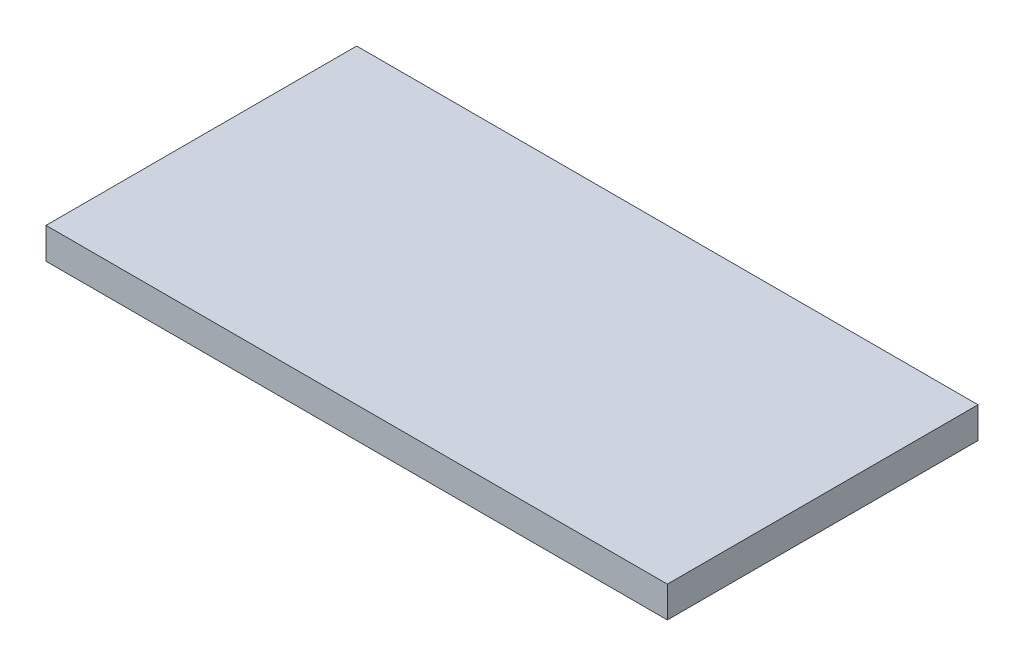
SolidWorks part; units mm, degrees
ref_plane "Front Plane" through (0, 0, 0) normal (0, 0, 1) x (1, 0, 0)
ref_plane "Top Plane" through (0, 0, 0) normal (0, 1, 0) x (1, 0, 0)
ref_plane "Right Plane" through (0, 0, 0) normal (1, 0, 0) x (0, 0, -1)
sketch "Sketch1" plane through (0, 0, 0) normal (0, 1, 0) x (1, 0, 0)
  line L1 (-1000, 500) -> (1000, 500)
  line L2 (-1000, 500) -> (-1000, -500)
  line L3 (-1000, -500) -> (1000, -500)
  line L4 (1000, 500) -> (1000, -500)
  line L5 (-1000, 500) -> (1000, -500) construction
  line L6 (-1000, -500) -> (1000, 500) construction
  point P0 (0, 0)
  dimension "D1" = 2000
  dimension "D2" = 1000
extrude "Boss-Extrude1" add sketch "Sketch1" along normal blind 100
sketch "Sketch2" plane through (0, 0, 0) normal (0, -1, 0) x (1, 0, 0)
  line L0 (-1000, 400) -> (-900, 400)
  line L1 (-1000, -500) -> (-1000, 500) construction
  line L2 (-900, 400) -> (-900, 500)
  line L3 (-1000, 500) -> (1000, 500) construction
  circle A0 centre (-900, 400) radius 63.8059
  point P8 (0, 0)
  point P10 (0, 0)
  dimension "D1" = 100
  dimension "D2" = 100
sketch "Sketch4" plane through (0, 0, 0) normal (0, -1, 0) x (1, 0, 0)
extrude "Cut-Extrude2" cut sketch "Sketch2" against normal mid plane 100 contours A0
sketch "Sketch7" plane through (0, 50, 0) normal (0, -1, 0) x (-1, 0, 0)
  line L0 (900, -400) -> (-1000, -400)
  line L1 (-1000, -500) -> (-1000, 500) construction
  line L2 (900, -400) -> (900, 500)
  line L3 (-1000, 500) -> (1000, 500) construction
  circle A0 centre (900, -400) radius 63.8059
